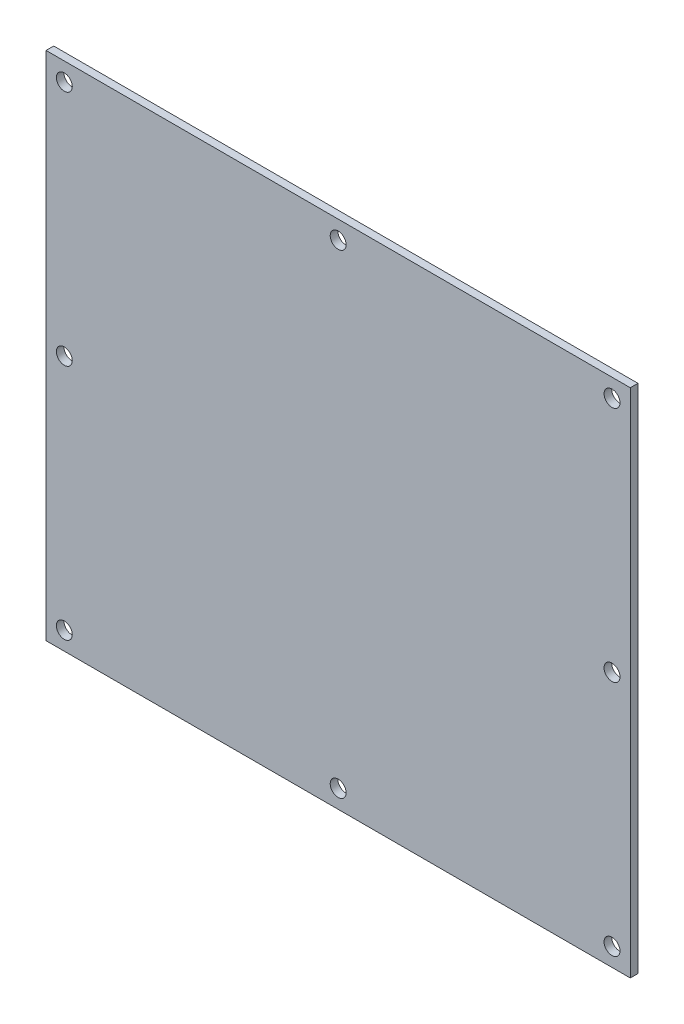
SolidWorks part; units mm, degrees
ref_plane "Front Plane" through (0, 0, 0) normal (0, 0, 1) x (1, 0, 0)
ref_plane "Top Plane" through (0, 0, 0) normal (0, 1, 0) x (1, 0, 0)
ref_plane "Right Plane" through (0, 0, 0) normal (1, 0, 0) x (0, 0, -1)
sketch "Sketch1" plane through (0, 0, 0) normal (0, 0, 1) x (1, 0, 0)
  line L1 (0, 0) -> (203.2, 0)
  line L2 (0, 0) -> (0, 177.8)
  line L3 (0, 177.8) -> (203.2, 177.8)
  line L4 (203.2, 0) -> (203.2, 177.8)
extrude "Boss-Extrude1" add sketch "Sketch1" along normal blind 2.667
sketch "Sketch2" plane through (0, 0, 0) normal (0, 0, 1) x (1, 0, 0)
  circle A0 centre (6.35, 6.35) radius 2.7686
  circle A1 centre (101.6, 6.35) radius 2.7686
  circle A2 centre (196.85, 6.35) radius 2.7686
  circle A3 centre (6.35, 88.9) radius 2.7686
  circle A4 centre (196.85, 88.9) radius 2.7686
  circle A5 centre (6.35, 171.45) radius 2.7686
  circle A6 centre (101.6, 171.45) radius 2.7686
  circle A7 centre (196.85, 171.45) radius 2.7686
extrude "Cut-Extrude1" cut sketch "Sketch2" along normal through all
